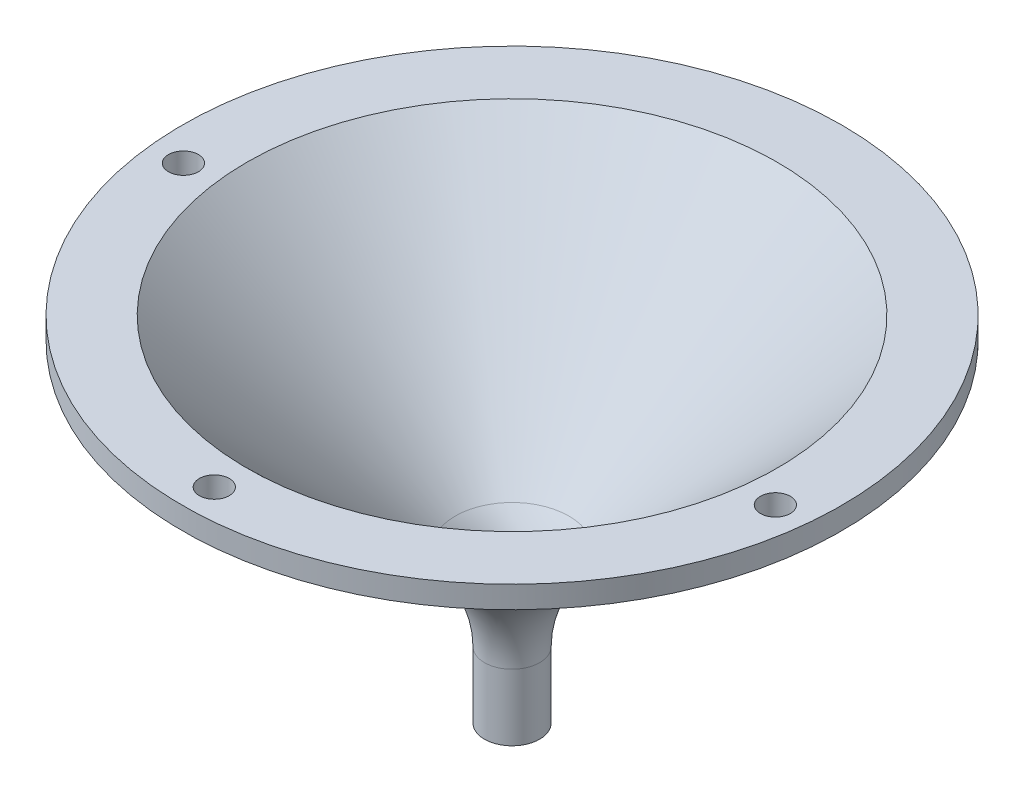
SolidWorks part; units mm, degrees
ref_plane "Front" through (0, 0, 0) normal (0, 0, 1) x (1, 0, 0)
ref_plane "Top" through (0, 0, 0) normal (0, 1, 0) x (1, 0, 0)
ref_plane "Right" through (0, 0, 0) normal (1, 0, 0) x (0, 0, -1)
sketch "Esquisse1" plane through (0, 0, 0) normal (0, 0, 1) x (1, 0, 0)
  line L1 (3.9688, 0) -> (3.9688, 9.5347)
  line L2 (8.97, 21.3723) -> (39.2387, 50.8)
  line L3 (39.2387, 50.8) -> (38.1, 50.8)
  line L4 (38.1, 50.8) -> (8.1763, 21.7077)
  line L5 (3.175, 9.87) -> (3.175, 0)
  line L8 (0, 0) -> (0, 63.5) construction
  line L10 (3.175, 0) -> (3.9688, 0)
  line L11 (0, 0) -> (13.1093, 0) construction
  arc A0 (8.1763, 21.7077) -> (3.175, 9.87) centre (19.685, 9.87) ccw
  arc A1 (3.9688, 9.5347) -> (8.97, 21.3723) centre (20.4788, 9.5347) cw
  point P9 (3.5719, 0)
  point P15 (3.9688, 16.51)
  dimension "D6" = 16.51
  dimension "D1" = 3.175
  dimension "D2" = 50.8
  dimension "D3" = 0.7937
  dimension "D4" = 0.7937
  dimension "D5" = 38.1
  dimension "D7" = 16.51
revolve "Révolution1" add sketch "Esquisse1" angle 360 about L8
sketch "Esquisse2" plane through (0, 0, 0) normal (0, 0, 1) x (1, 0, 0)
  line L7 (0, 0) -> (0, 50.8) construction
  line L8 (39.2387, 50.8) -> (-39.2387, 50.8) construction
  line L9 (39.2387, 50.8) -> (47.3667, 50.8)
  line L10 (47.3667, 50.8) -> (47.3667, 47.625)
  line L11 (47.3667, 47.625) -> (35.973, 47.625)
  line L12 (8.97, 21.3723) -> (39.2387, 50.8) construction
  line L13 (35.973, 47.625) -> (39.2387, 50.8)
  dimension "D1" = 3.175
  dimension "D2" = 8.128
revolve "Révolution2" add sketch "Esquisse2" angle 360 about L7
sketch "Esquisse3" plane through (0, 50.8, 0) normal (0, 1, 0) x (1, 0, 0)
  circle A0 centre (0, 0) radius 42.7947 construction
  circle A1 centre (0, 0) radius 47.3667 construction
  circle A2 centre (0, -42.7947) radius 2.15
  circle A3 centre (-42.5364, -4.6947) radius 2.15
  circle A4 centre (42.5364, -4.6947) radius 2.15
  dimension "D1" = 4.572
  dimension "D2" = 4.3
  dimension "D3" = 38.1
extrude "Enlèv. mat.-Extru.1" cut sketch "Esquisse3" against normal through all
sketch "Esquisse4" plane through (0, 0, 0) normal (0, -1, 0) x (1, 0, 0)
  line L1 (-0.6, 3.9231) -> (0.6, 3.9231)
  line L2 (-0.6, 3.9231) -> (-0.6, -3.9231)
  line L3 (-0.6, -3.9231) -> (0.6, -3.9231)
  line L4 (0.6, 3.9231) -> (0.6, -3.9231)
  circle A0 centre (0, 0) radius 3.9688 construction
  point P6 (0, 0)
  point P7 (0, 0)
  point P8 (0, 0)
  point P9 (0, 0)
  point P10 (0, 0)
  dimension "D1" = 1.2
extrude "Boss.-Extru.1" add sketch "Esquisse4" against normal blind 6.35
